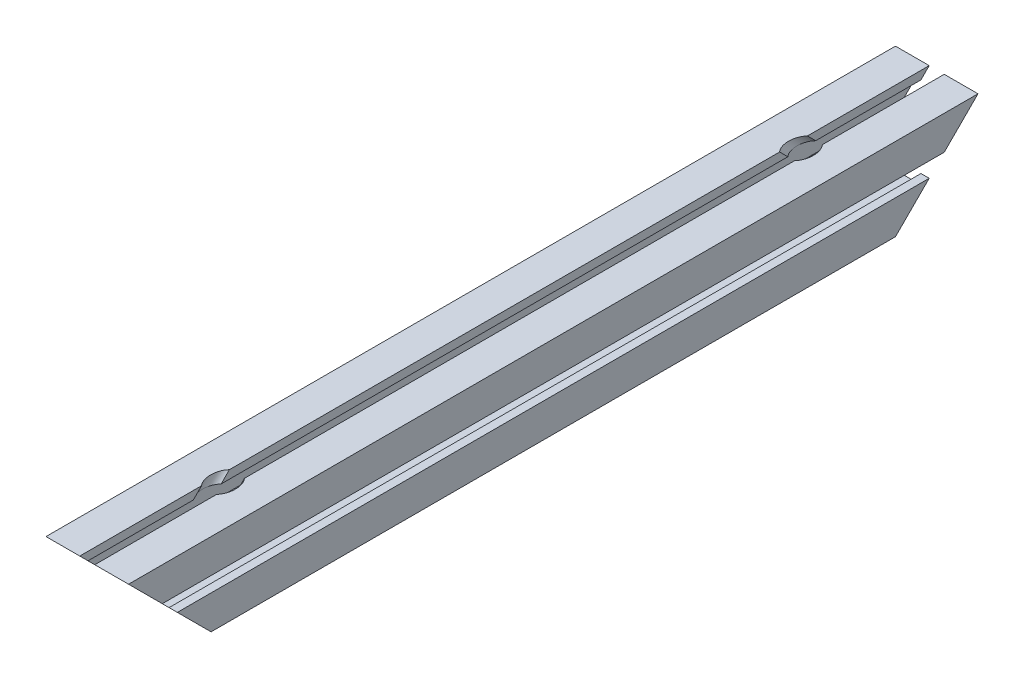
SolidWorks part; units mm, degrees
material "6061 Alloy"
ref_plane "Front Plane" through (0, 0, 0) normal (0, 0, 1) x (1, 0, 0)
ref_plane "Top Plane" through (0, 0, 0) normal (0, 1, 0) x (1, 0, 0)
ref_plane "Right Plane" through (0, 0, 0) normal (1, 0, 0) x (0, 0, -1)
sketch "Sketch1" plane through (0, 0, 0) normal (0, 0, 1) x (1, 0, 0)
  line L88 (-18, -4.1) -> (-22.5, -4.1)
  line L89 (-22.5, -4.1) -> (-22.5, -22.5)
  line L90 (-22.5, -22.5) -> (-4.1, -22.5)
  line L91 (-4.1, -22.5) -> (-4.1, -18)
  line L92 (-4.1, -18) -> (-6.8, -18)
  line L93 (-6.8, -18) -> (-6.8, -9.5)
  line L94 (-6.8, -9.5) -> (-4.5, -7.2)
  line L95 (-4.5, -7.2) -> (4.5, -7.2)
  line L96 (4.5, -7.2) -> (6.8, -9.5)
  line L97 (6.8, -9.5) -> (6.8, -18)
  line L98 (6.8, -18) -> (4.1, -18)
  line L99 (4.1, -18) -> (4.1, -22.5)
  line L100 (4.1, -22.5) -> (22.5, -22.5)
  line L101 (22.5, -22.5) -> (22.5, -4.1)
  line L102 (22.5, -4.1) -> (18, -4.1)
  line L103 (18, -4.1) -> (18, -6.8)
  line L104 (18, -6.8) -> (9.5, -6.8)
  line L105 (9.5, -6.8) -> (7.2, -4.5)
  line L106 (7.2, -4.5) -> (7.2, 4.5)
  line L107 (7.2, 4.5) -> (9.5, 6.8)
  line L108 (9.5, 6.8) -> (18, 6.8)
  line L109 (18, 6.8) -> (18, 4.1)
  line L110 (18, 4.1) -> (22.5, 4.1)
  line L111 (22.5, 4.1) -> (22.5, 22.5)
  line L112 (22.5, 22.5) -> (4.1, 22.5)
  line L113 (4.1, 22.5) -> (4.1, 18)
  line L114 (4.1, 18) -> (6.8, 18)
  line L115 (6.8, 18) -> (6.8, 9.5)
  line L116 (6.8, 9.5) -> (4.5, 7.2)
  line L117 (4.5, 7.2) -> (-4.5, 7.2)
  line L118 (-4.5, 7.2) -> (-6.8, 9.5)
  line L119 (-6.8, 9.5) -> (-6.8, 18)
  line L120 (-6.8, 18) -> (-4.1, 18)
  line L121 (-4.1, 18) -> (-4.1, 22.5)
  line L122 (-4.1, 22.5) -> (-22.5, 22.5)
  line L123 (-22.5, 22.5) -> (-22.5, 4.1)
  line L124 (-22.5, 4.1) -> (-18, 4.1)
  line L125 (-18, 4.1) -> (-18, 6.8)
  line L126 (-18, 6.8) -> (-9.5, 6.8)
  line L127 (-9.5, 6.8) -> (-7.2, 4.5)
  line L128 (-7.2, 4.5) -> (-7.2, -4.5)
  line L129 (-7.2, -4.5) -> (-9.5, -6.8)
  line L130 (-9.5, -6.8) -> (-18, -6.8)
  line L131 (-18, -6.8) -> (-18, -4.1)
  circle A5 centre (14.65, -14.65) radius 6
  circle A6 centre (-14.65, -14.65) radius 6
  circle A7 centre (0, 0) radius 3.75
  circle A8 centre (14.65, 14.65) radius 6
  circle A9 centre (-14.65, 14.65) radius 6
extrude "Extrude1" add sketch "Sketch1" along normal blind 231.5775 and the other way blind 231.5775
sketch "Sketch2" plane through (22.5, 0, 0) normal (1, 0, 0) x (0, 0, -1)
  line L0 (-231.5775, 4.1) -> (-231.5775, 22.5) construction
  line L1 (-231.5775, 4.1) -> (-231.5775, 22.5)
  line L2 (231.5775, -22.5) -> (-231.5775, -22.5) construction
  line L3 (231.5775, -22.5) -> (-231.5775, -22.5)
  line L4 (-231.5775, 22.5) -> (-186.5775, -22.5)
  line L5 (-186.5775, -22.5) -> (-231.5775, -22.5)
  line L6 (-231.5775, -22.5) -> (-231.5775, 22.5)
  line L7 (231.5775, 22.5) -> (231.5775, -22.5)
  line L8 (231.5775, -22.5) -> (186.5775, -22.5)
  line L9 (186.5775, -22.5) -> (231.5775, 22.5)
  line M2 (-231.5775, 22.5) -> (-231.5775, 4.1)
  line M3 (-231.5775, 4.1) -> (231.5775, 4.1)
  line M4 (231.5775, 4.1) -> (231.5775, 22.5)
  dimension "D1" = 45
  dimension "D2" = 45
extrude "Extrude2" cut sketch "Sketch2" against normal through all contours L6 L3 L4 M3 | L4 M2 M3 | L9 L3 L7 M3 | L9 M3 M4
ref_plane "Plane1" through (0, -89.2723, 89.2723) normal (0, -0.7071, 0.7071) x (1, 0, 0)
sketch "Sketch3" plane through (0, -104.5387, 104.5387) normal (0, -0.7071, 0.7071) x (1, 0, 0)
  line L0 (22.5, 179.6599) -> (22.5, 153.6384) construction
  line L1 (22.5, 179.6599) -> (4.1, 179.6599) construction
  circle A0 centre (0, 127.3359) radius 4.25
  dimension "D3" = 8.5
  dimension "D1" = 22.5
  dimension "D2" = 52.324
extrude "Extrude3" cut sketch "Sketch3" against normal through all
sketch "Sketch4" plane through (0, -89.2723, 89.2723) normal (0, -0.7071, 0.7071) x (1, 0, 0)
  circle A0 centre (0, 127.3359) radius 4.25 construction
  circle A1 centre (0, 127.3359) radius 4.25
  circle A2 centre (0, 127.3359) radius 6.75
  dimension "D1" = 13.5
extrude "Extrude4" cut sketch "Sketch4" against normal through all
mirror "Mirror1" about plane through (0, 0, 0) normal (0, 0, 1) of "Extrude3", "Extrude4"
